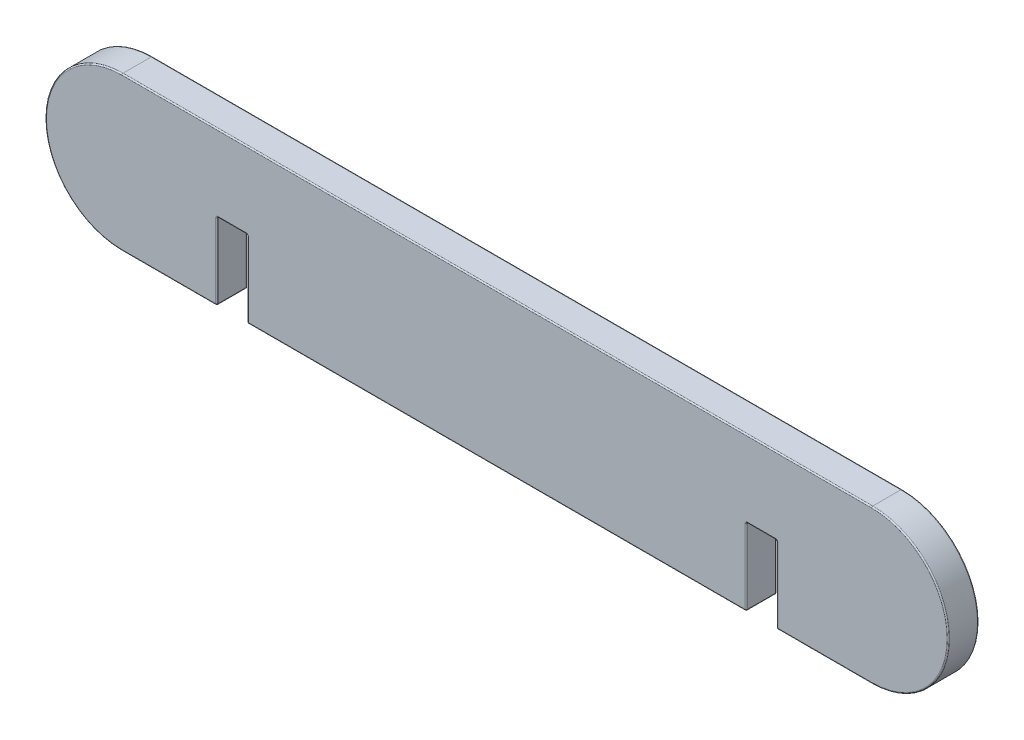
SolidWorks part; units mm, degrees
ref_plane "Plano frontal" through (0, 0, 0) normal (0, 0, 1) x (1, 0, 0)
ref_plane "Plano superior" through (0, 0, 0) normal (0, 1, 0) x (1, 0, 0)
ref_plane "Plano direito" through (0, 0, 0) normal (1, 0, 0) x (0, 0, -1)
sketch "Esboço1" plane through (0, 0, 0) normal (0, 0, 1) x (1, 0, 0)
  line L0 (-192.6141, 152.8206) -> (-131.0141, 152.8206) construction
  line L1 (-184.8141, 152.8206) -> (-182.3141, 152.8206)
  line L2 (-184.8141, 152.8206) -> (-184.8141, 143.5663)
  line L3 (-184.8141, 143.5663) -> (-182.3141, 143.5663)
  line L4 (-182.3141, 152.8206) -> (-182.3141, 143.5663)
  line L5 (-198.9141, 152.8206) -> (-124.7141, 152.8206) construction
  line L13 (-141.3141, 152.8206) -> (-138.8141, 152.8206)
  line L14 (-141.3141, 152.8206) -> (-141.3141, 143.5663)
  line L15 (-141.3141, 143.5663) -> (-138.8141, 143.5663)
  line L16 (-138.8141, 152.8206) -> (-138.8141, 143.5663)
  line L17 (-192.6141, 159.1206) -> (-131.0141, 159.1206)
  line L18 (-192.6141, 146.5206) -> (-131.0141, 146.5206)
  arc A1 (-192.6141, 159.1206) -> (-192.6141, 146.5206) centre (-192.6141, 152.8206) ccw
  arc A2 (-131.0141, 146.5206) -> (-131.0141, 159.1206) centre (-131.0141, 152.8206) ccw
  point P20 (-161.8141, 152.8206)
  dimension "D1" = 74.2
  dimension "D5" = 6.3
  dimension "D2" = 2.5
  dimension "D3" = 41
  dimension "D4" = 20.5
extrude "Ressalto-extrusão1" add sketch "Esboço1" along normal blind 2.5 contours L18 A2 L17 A1 L2 L1 L4 L14 L13 L16
fillet "Filete1" radius 0.1 32 edges at (-184.8141, 146.5206, 1.25) (-184.8141, 152.8206, 1.25) (-182.3141, 152.8206, 1.25) (-182.3141, 146.5206, 1.25) (-141.3141, 146.5206, 1.25) (-141.3141, 152.8206, 1.25) (-138.8141, 152.8206, 1.25) (-138.8141, 146.5206, 1.25) (-138.8141, 149.6706, 0) (-138.8141, 149.6706, 2.5) (-140.0641, 152.8206, 0) (-140.0641, 152.8206, 2.5) (-141.3141, 149.6706, 0) (-141.3141, 149.6706, 2.5) (-161.8141, 146.5206, 2.5) (-161.8141, 146.5206, 0) (-182.3141, 149.6706, 0) (-182.3141, 149.6706, 2.5) (-183.5641, 152.8206, 0) (-183.5641, 152.8206, 2.5) (-184.8141, 149.6706, 0) (-184.8141, 149.6706, 2.5) (-188.7141, 146.5206, 2.5) (-188.7141, 146.5206, 0) (-198.9141, 152.8206, 0) (-198.9141, 152.8206, 2.5) (-161.8141, 159.1206, 0) (-161.8141, 159.1206, 2.5) (-124.7141, 152.8206, 0) (-124.7141, 152.8206, 2.5) (-134.9141, 146.5206, 2.5) (-134.9141, 146.5206, 0)
